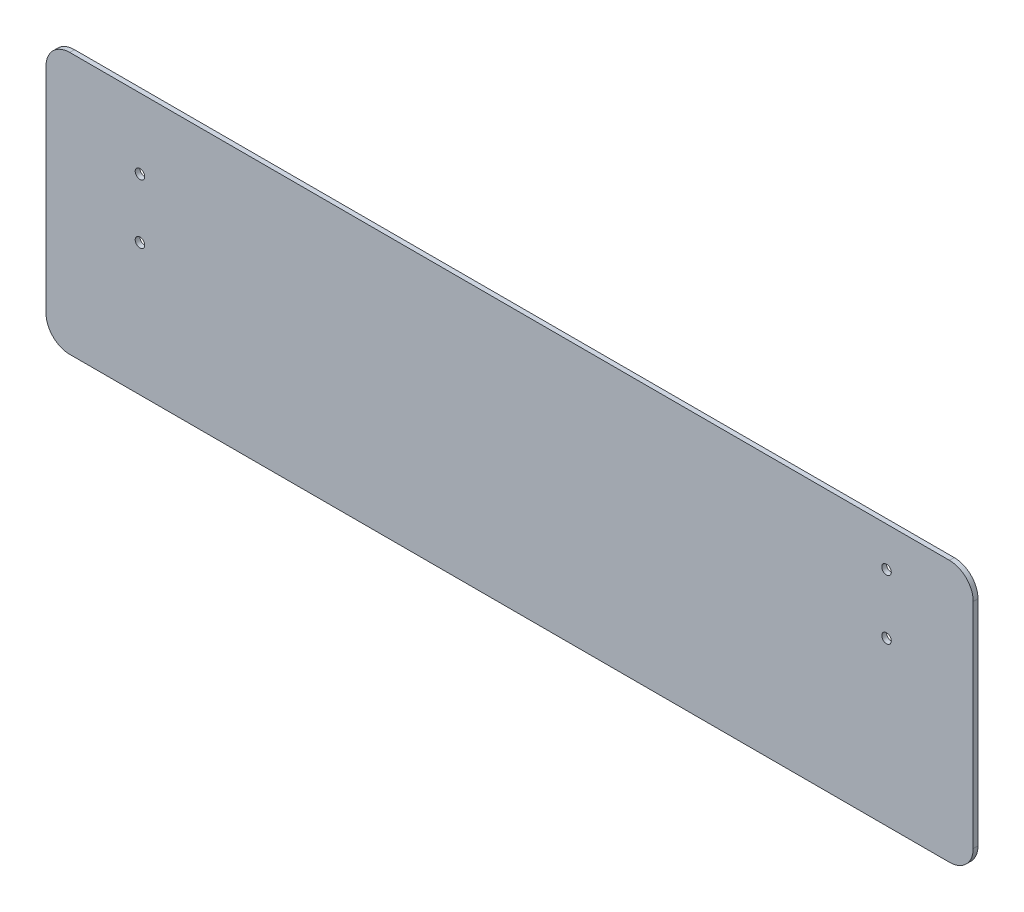
SolidWorks part; units mm, degrees
ref_plane "Plan de face" through (0, 0, 0) normal (0, 0, 1) x (1, 0, 0)
ref_plane "Plan de dessus" through (0, 0, 0) normal (0, 1, 0) x (1, 0, 0)
ref_plane "Plan de droite" through (0, 0, 0) normal (1, 0, 0) x (0, 0, -1)
sketch "Esquisse1" plane through (0, 0, 0) normal (0, 0, 1) x (1, 0, 0)
  line L0 (0, 55) -> (0, -34.6652) construction
  line L1 (-185, 55) -> (185, 55)
  line L2 (-195, 45) -> (-195, -45)
  line L3 (-185, -55) -> (185, -55)
  line L4 (195, 45) -> (195, -45)
  line L5 (-195, 0) -> (102.5006, 0) construction
  arc A0 (185, -55) -> (195, -45) centre (185, -45) ccw
  arc A1 (185, 55) -> (195, 45) centre (185, 45) cw
  arc A2 (-185, 55) -> (-195, 45) centre (-185, 45) ccw
  arc A3 (-195, -45) -> (-185, -55) centre (-185, -45) ccw
  point P13 (195, 55)
  point P16 (-195, 55)
  point P19 (-195, -55)
  dimension "D3" = 10
  dimension "D4" = 10
  dimension "D1" = 390
  dimension "D2" = 110
extrude "Boss.-Extru.1" add sketch "Esquisse1" along normal blind 2
sketch "Esquisse3" plane through (0, 0, 0) normal (0, 0, -1) x (-1, 0, 0)
  line L0 (0, 55) -> (0, 117.6235) construction
  line L1 (-185, 55) -> (185, 55) construction
sketch "Esquisse5" plane through (0, 0, 2) normal (0, 0, 1) x (1, 0, 0)
  line L4 (195, -45) -> (195, 45)
  line L5 (185, 55) -> (-185, 55)
  line L6 (-195, 45) -> (-195, -45)
  line L7 (-185, -55) -> (185, -55)
  line L8 (195, -45) -> (195, 45)
  line L9 (185, 55) -> (-185, 55)
  line L10 (-195, 45) -> (-195, -45)
  line L11 (-185, -55) -> (185, -55)
  arc A4 (185, -55) -> (195, -45) centre (185, -45) ccw
  arc A5 (195, 45) -> (185, 55) centre (185, 45) ccw
  arc A6 (-185, 55) -> (-195, 45) centre (-185, 45) ccw
  arc A7 (-195, -45) -> (-185, -55) centre (-185, -45) ccw
  arc A8 (185, -55) -> (195, -45) centre (185, -45) ccw
  arc A9 (195, 45) -> (185, 55) centre (185, 45) ccw
  arc A10 (-185, 55) -> (-195, 45) centre (-185, 45) ccw
  arc A11 (-195, -45) -> (-185, -55) centre (-185, -45) ccw
  dimension "D1" = 0
sketch "Esquisse6" plane through (0, 0, 2) normal (0, 0, 1) x (1, 0, 0)
  circle A2 centre (158.5226, 13.3763) radius 2 construction
  circle A3 centre (158.5226, 38.3763) radius 2 construction
  circle A4 centre (-155.4774, 25.5107) radius 2 construction
  circle A5 centre (158.5226, 13.3763) radius 2
  circle A6 centre (158.5226, 38.3763) radius 2
  circle A7 centre (-155.4774, 25.5107) radius 2
  circle A8 centre (-155.4774, 0.5107) radius 2 construction
  circle A9 centre (-155.4774, 0.5107) radius 2
extrude "Enlèv. mat.-Extru.1" cut sketch "Esquisse6" against normal blind 10
